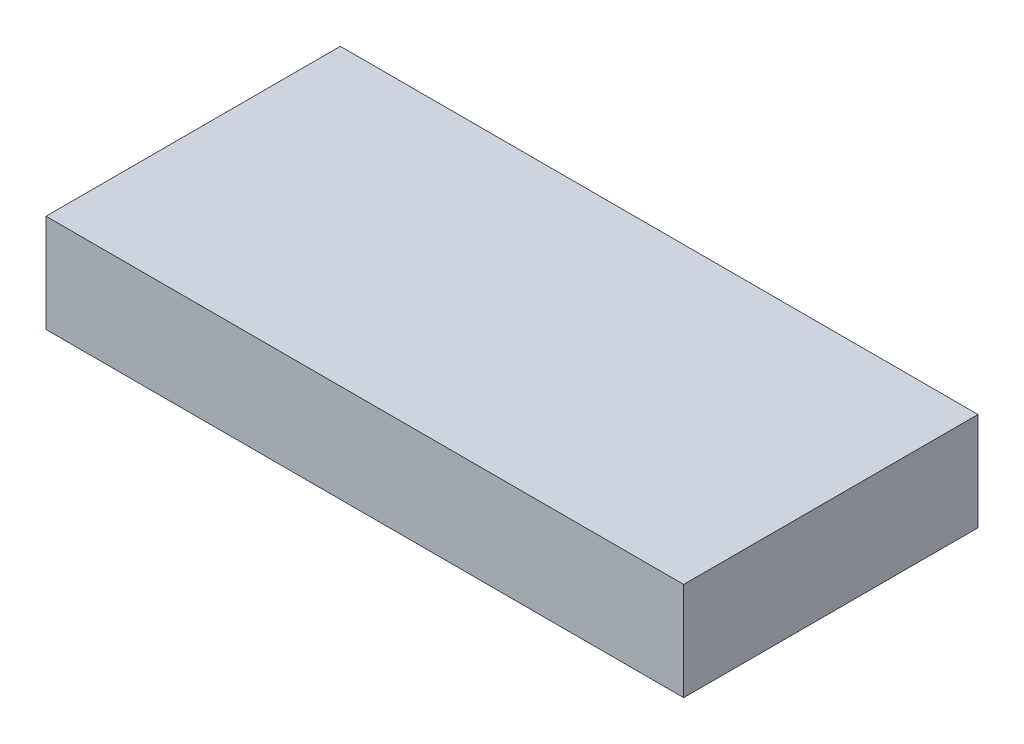
SolidWorks part; units mm, degrees
ref_plane "Front Plane" through (0, 0, 0) normal (0, 0, 1) x (1, 0, 0)
ref_plane "Top Plane" through (0, 0, 0) normal (0, 1, 0) x (1, 0, 0)
ref_plane "Right Plane" through (0, 0, 0) normal (1, 0, 0) x (0, 0, -1)
sketch "Sketch1" plane through (0, 0, 0) normal (0, 1, 0) x (1, 0, 0)
  line L1 (-6.5, 3) -> (6.5, 3)
  line L2 (-6.5, 3) -> (-6.5, -3)
  line L3 (-6.5, -3) -> (6.5, -3)
  line L4 (6.5, 3) -> (6.5, -3)
  line L5 (-6.5, 3) -> (6.5, -3) construction
  line L6 (-6.5, -3) -> (6.5, 3) construction
  point P0 (0, 0)
  dimension "D1" = 13
  dimension "D2" = 6
extrude "Boss-Extrude1" add sketch "Sketch1" along normal blind 2 contours L2 L1 L4 L3
